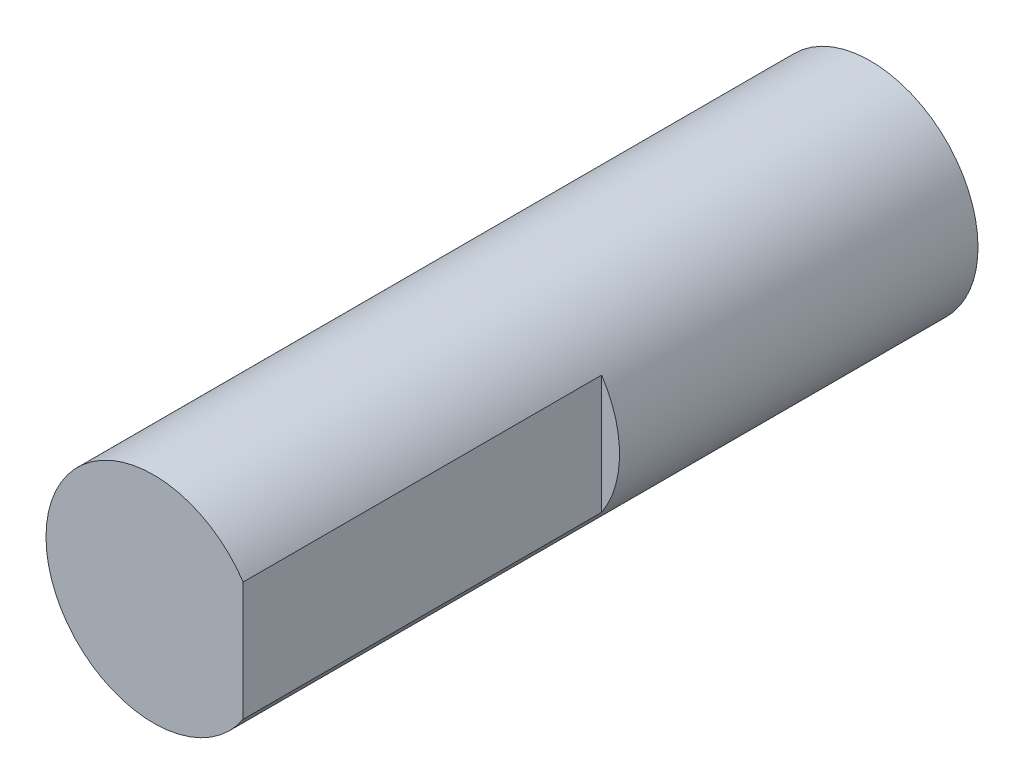
SolidWorks part; units mm, degrees
material "1060 Alloy"
ref_plane "Frontal Plane" through (0, 0, 0) normal (0, 0, 1) x (1, 0, 0)
ref_plane "Horizontal Plane" through (0, 0, 0) normal (0, 1, 0) x (1, 0, 0)
ref_plane "Profile Plane" through (0, 0, 0) normal (1, 0, 0) x (0, 0, -1)
sketch "Sketch1" plane through (0, 0, 0) normal (0, 0, 1) x (1, 0, 0)
  circle A0 centre (0, 0) radius 3
  dimension "D1" = 6
extrude "Boss-Extrude1" add sketch "Sketch1" along normal blind 20
sketch "Sketch2" plane through (0, 0, 20) normal (0, 0, 1) x (1, 0, 0)
  line L0 (2.5, 1.6583) -> (2.5, -1.6583)
  circle A0 centre (0, 0) radius 3 construction
  arc A1 (2.5, -1.6583) -> (2.5, 1.6583) centre (0, 0) ccw
  dimension "D1" = 2.5
extrude "Cut-Extrude1" cut sketch "Sketch2" against normal blind 10
equation "\"D1@Boss-Extrude1\"=\"EncoderShaftL\"+5"
equation "\"PinDiameter\"= 0"
equation "\"WallThickness\"= 0.5cm"
equation "\"BottomPlateX\"= 3ft"
equation "\"ActuatorL\"= 35cm"
equation "\"ActuatorPinD\"= 6.35mm"
equation "\"ActuatorPinL\"= 15cm"
equation "\"Box-X\"= 40cm"
equation "\"Box-Z\"= 20cm"
equation "\"Box-Y\"= 30cm"
equation "\"RotaryUnionThickness\"= 1cm"
equation "\"ArmPlateThickness\"= .125in"
equation "\"ArmPlateX\"= 18in"
equation "\"Arm1X\"= 5cm"
equation "\"Arm1L\"= 60cm"
equation "\"Arm2GAP\"= 5cm"
equation "\"Arm2L\"= 60cm"
equation "\"Arm2H\"= 5cm"
equation "\"Arm2Extension\"= 5cm"
equation "\"Arm3GAP\"= 5cm"
equation "\"Arm3L\"= 60cm"
equation "\"Arm3H\"= 5cm"
equation "\"Pin1-2L\"= \"Arm2GAP\" + (2 * \"WallThickness\")"
equation "\"Pin2-3L\"= \"Arm3GAP\" + (4 * \"WallThickness\")"
equation "\"DCMotor1D\"= 65mm"
equation "\"DCMotor1L\"= 215mm"
equation "\"DCMotor1ShaftL\"= 30mm"
equation "\"DCMotor2X\"= 68mm"
equation "\"DCMotor2D\"= 65mm"
equation "\"DCMotor2L\"= 208mm"
equation "\"DCMotor2ShaftL\"= 39mm"
equation "\"DCMotor2ShaftD\"= 15mm"
equation "\"BenchDepth\"= 5cm"
equation "\"BenchH\"= 10cm"
equation "\"BenchL\"= 15cm"
equation "\"PillowBlockW\"= 5cm"
equation "\"PillowBlockCenterH\"= \"DCMotor2X\"/2"
equation "\"EncoderRadius\"= 19mm"
equation "\"EncoderL\"= 33mm"
equation "\"EncoderShaftL\"= 15mm"
equation "\"EncoderShaftRadius\"= 3mm"
equation "\"BeltLockH\"= \"PulleyH\" + 11.885mm - (\"SlidePlateThickness\" + \"SlidePlateClearance\" + 15mm + 5mm)"
equation "\"BeltW\"= .375in"
equation "\"BeltThickness\"= 2mm"
equation "\"BeltL\"= 1500mm + \"BoxX\""
equation "\"HeadstoneThickness\"= 7.5mm"
equation "\"MotorShaftL\"= 18mm"
equation "\"MotorShaftRadius\"= 2.5mm"
equation "\"MotorRadius\"= 21mm"
equation "\"MotorL\"= 83mm"
equation "\"PulleyShaft2L\"= \"BoxX\"+ 3mm"
equation "\"PulleyShaftL\"= \"BoxX\" + 5cm"
equation "\"PulleyShaftDiameter\"= 8mm"
equation "\"PulleyH\"= 2cm + \"SlidePlateClearance\" + (\"SlidePlateThickness\"/2)"
equation "\"PulleyRadius\"= 15.1mm"
equation "\"BoxH\"= 2cm + \"SlidePlateClearance\" + \"SlidePlateThickness\" + 3cm"
equation "\"BoxX\"= \"RailGap\" + 30mm"
equation "\"BoxThickness\"= .5cm"
equation "\"SlidePlateClearance\"= 1cm"
equation "\"SlidePlateThickness\"= 3mm"
equation "\"SlidePlateW\"= 14cm"
equation "\"SlidePlateL\"= 14cm"
equation "\"RailGap\"= 5cm"
equation "\"BaseThickness\"= 1cm"
equation "\"BaseW\"= 30cm"
equation "\"BaseL\"= 1700mm"
